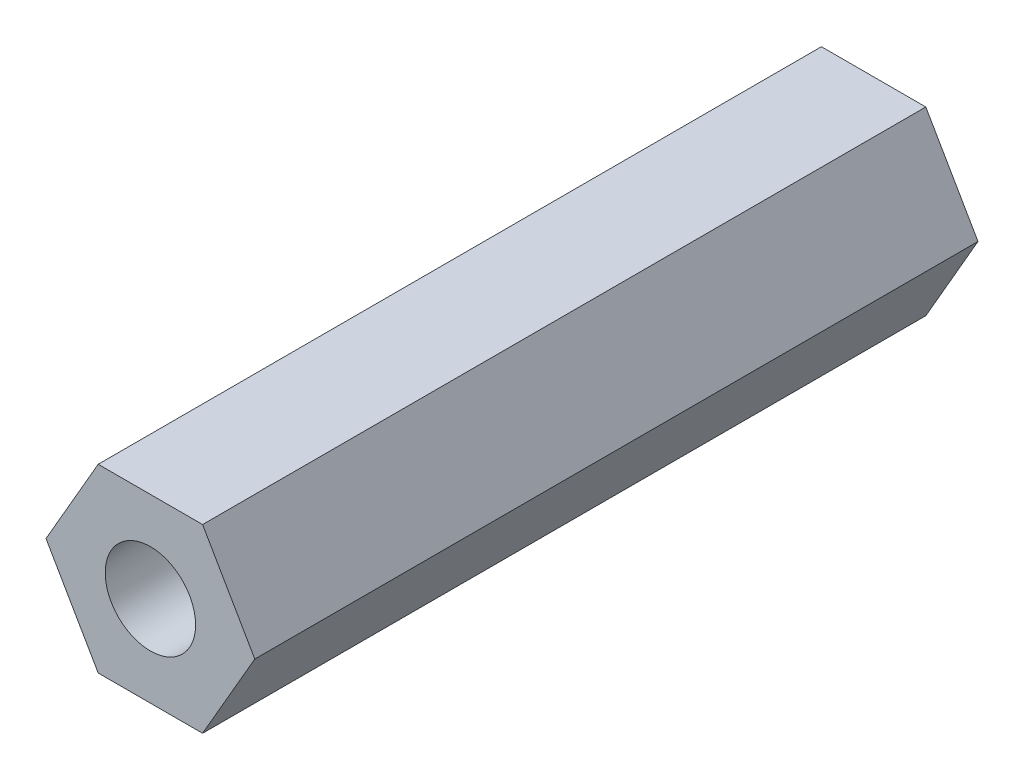
SolidWorks part; units mm, degrees
material "1060 Alloy"
ref_plane "Front Plane" through (0, 0, 0) normal (0, 0, 1) x (1, 0, 0)
ref_plane "Top Plane" through (0, 0, 0) normal (0, 1, 0) x (1, 0, 0)
ref_plane "Right Plane" through (0, 0, 0) normal (1, 0, 0) x (0, 0, -1)
sketch "Sketch1" plane through (0, 0, 0) normal (0, 0, 1) x (1, 0, 0)
  line L1 (3.6662, 6.35) -> (-3.6662, 6.35)
  line L2 (-3.6662, 6.35) -> (-7.3323, 0)
  line L3 (-7.3323, 0) -> (-3.6662, -6.35)
  line L4 (-3.6662, -6.35) -> (3.6662, -6.35)
  line L5 (3.6662, -6.35) -> (7.3323, 0)
  line L6 (7.3323, 0) -> (3.6662, 6.35)
  circle A0 centre (0, 0) radius 6.35 construction
  circle A1 centre (0, 0) radius 3.175
  dimension "D2" = 6.35
  dimension "D1" = 12.7
extrude "Boss-Extrude1" add sketch "Sketch1" along normal blind 50.8
